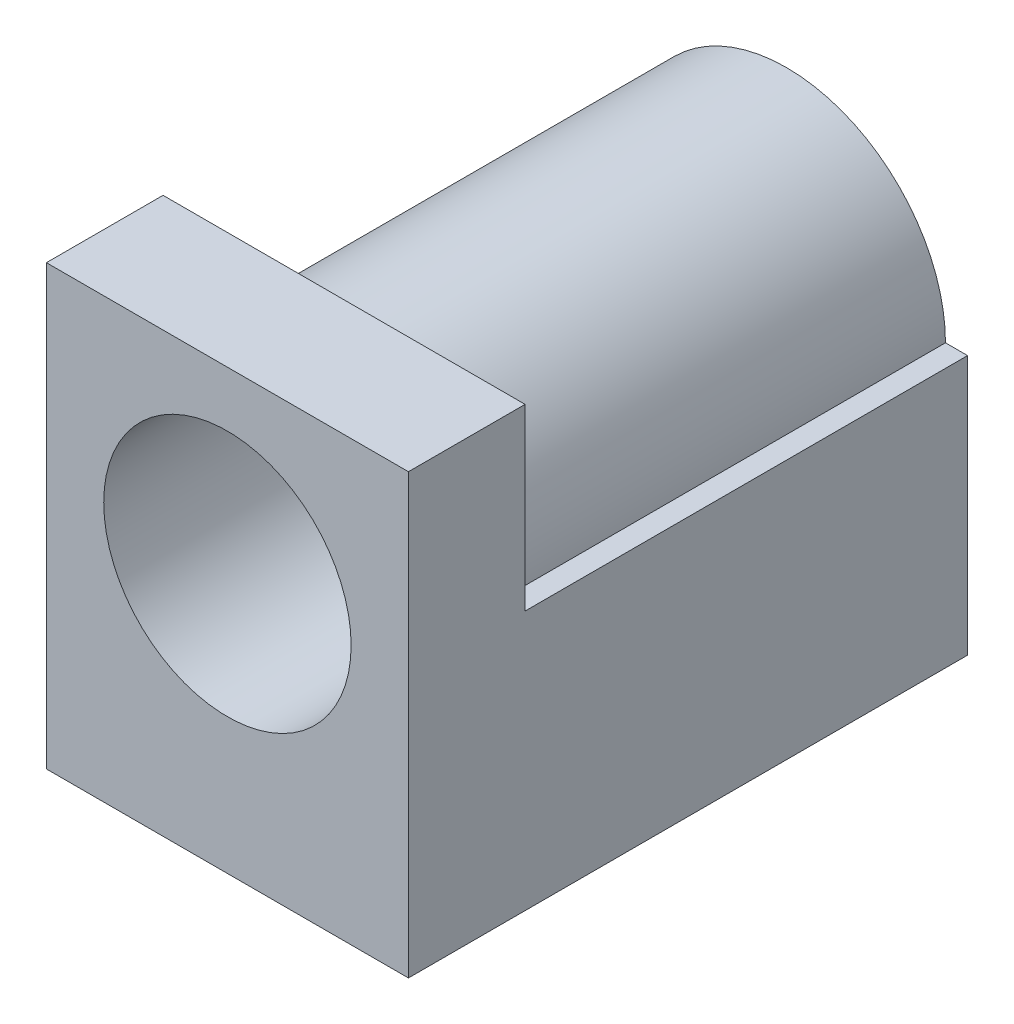
SolidWorks part; units mm, degrees
ref_plane "Front Plane" through (0, 0, 0) normal (0, 0, 1) x (1, 0, 0)
ref_plane "Top Plane" through (0, 0, 0) normal (0, 1, 0) x (1, 0, 0)
ref_plane "Right Plane" through (0, 0, 0) normal (1, 0, 0) x (0, 0, -1)
sketch "Sketch1" plane through (0, 0, 0) normal (0, 0, 1) x (1, 0, 0)
  line L0 (-4.5, 5.45) -> (4.5, -5.45) construction
  line L1 (-4.5, 5.45) -> (4.5, 5.45)
  line L2 (-4.5, 5.45) -> (-4.5, -5.45)
  line L3 (-4.5, -5.45) -> (4.5, -5.45)
  line L4 (4.5, 5.45) -> (4.5, -5.45)
  dimension "D1" = 9
  dimension "D2" = 10.9
extrude "Boss-Extrude1" add sketch "Sketch1" along normal blind 2.9
sketch "Sketch2" plane through (0, 0, 0) normal (0, 0, -1) x (-1, 0, 0)
  line L0 (0, 1) -> (0, 0) construction
  line L1 (-4.5, 5.45) -> (4.5, 5.45) construction
  line L2 (-3.95, 1) -> (-4.5, 1)
  line L3 (-4.5, -5.45) -> (-4.5, 5.45) construction
  line L4 (3.95, 1) -> (4.5, 1)
  line L5 (4.5, 5.45) -> (4.5, -5.45) construction
  line L6 (-4.5, 1) -> (-4.5, -5.45)
  line L7 (-4.5, -5.45) -> (4.5, -5.45)
  line L8 (4.5, -5.45) -> (4.5, 1)
  arc A0 (3.95, 1) -> (-3.95, 1) centre (0, 1) ccw
  point P5 (0, 4.95)
  point P7 (0, 5.45)
  dimension "D1" = 7.9
  dimension "D2" = 0.5
extrude "Boss-Extrude2" add sketch "Sketch2" along normal blind 11
sketch "Sketch3" plane through (0, 0, 2.9) normal (0, 0, 1) x (1, 0, 0)
  circle A0 centre (0, 1) radius 3.075
  arc A1 (3.95, 1) -> (-3.95, 1) centre (0, 1) ccw construction
  dimension "D1" = 6.15
extrude "Cut-Extrude1" cut sketch "Sketch3" against normal blind 9
